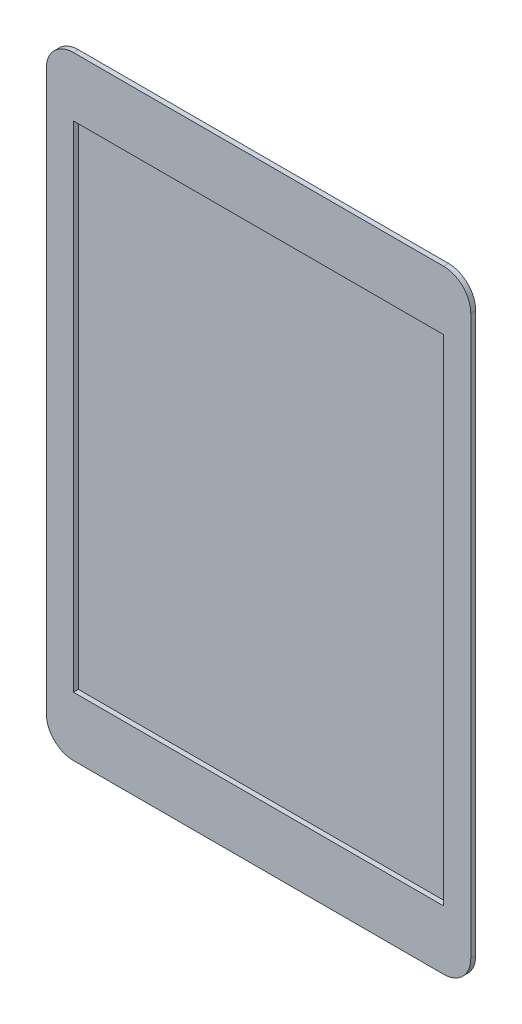
SolidWorks part; units mm, degrees
material "A-Glass Fiber"
ref_plane "Front Plane" through (0, 0, 0) normal (0, 0, 1) x (1, 0, 0)
ref_plane "Top Plane" through (0, 0, 0) normal (0, 1, 0) x (1, 0, 0)
ref_plane "Right Plane" through (0, 0, 0) normal (1, 0, 0) x (0, 0, -1)
sketch "Sketch2" plane through (0, 0, 0) normal (0, 0, 1) x (1, 0, 0)
  line L1 (-75.05, 124.3) -> (75.05, 124.3)
  line L2 (-86.05, 113.3) -> (-86.05, -113.3)
  line L3 (-75.05, -124.3) -> (75.05, -124.3)
  line L4 (86.05, 113.3) -> (86.05, -113.3)
  line L5 (-86.05, 124.3) -> (86.05, -124.3) construction
  line L6 (-86.05, -124.3) -> (86.05, 124.3) construction
  line L7 (-75.05, 100.3) -> (75.05, 100.3)
  line L8 (-75.05, 100.3) -> (-75.05, -100.3)
  line L9 (-75.05, -100.3) -> (75.05, -100.3)
  line L10 (75.05, 100.3) -> (75.05, -100.3)
  line L11 (-75.05, 100.3) -> (75.05, -100.3) construction
  line L12 (-75.05, -100.3) -> (75.05, 100.3) construction
  arc A0 (-86.05, -113.3) -> (-75.05, -124.3) centre (-75.05, -113.3) ccw
  arc A1 (75.05, -124.3) -> (86.05, -113.3) centre (75.05, -113.3) ccw
  arc A2 (75.05, 124.3) -> (86.05, 113.3) centre (75.05, 113.3) cw
  arc A3 (-75.05, 124.3) -> (-86.05, 113.3) centre (-75.05, 113.3) ccw
  point P0 (0, 0)
  point P18 (0, 0)
  dimension "D3" = 11
  dimension "D1" = 248.6
  dimension "D2" = 172.1
  dimension "D4" = 200.6
  dimension "D5" = 150.1
extrude "Boss-Extrude1" add sketch "Sketch2" along normal blind 2
sketch "Sketch3" plane through (0, 0, 0) normal (0, 0, 1) x (1, 0, 0)
  line L1 (-75.05, -100.3) -> (75.05, -100.3)
  line L2 (-75.05, -100.3) -> (-75.05, 100.3)
  line L3 (-75.05, 100.3) -> (75.05, 100.3)
  line L4 (75.05, -100.3) -> (75.05, 100.3)
  line L5 (-75.05, -100.3) -> (75.05, 100.3) construction
  line L6 (-75.05, 100.3) -> (75.05, -100.3) construction
  point P0 (0, 0)
extrude "Boss-Extrude2" add sketch "Sketch3" against normal blind 0.1 separate body
ref_plane "Plane1" through (0, 0, 0) normal (0, 0, -1) x (-1, 0, 0)
sketch "Sketch4" plane through (0, 0, 0) normal (0, 0, -1) x (-1, 0, 0)
  line L0 (75.05, -124.3) -> (-75.05, -124.3) construction
  circle A0 centre (0, -111.8) radius 4.75
  circle A1 centre (0, -111.8) radius 5.5
  dimension "D2" = 9.5
  dimension "D3" = 11
  dimension "D1" = 12.5
extrude "Cut-Extrude1" cut sketch "Sketch4" against normal blind 1
fillet "Fillet1" radius 0.001 1 edges at (-4.75, -111.8, 0)
fillet "Fillet2" radius 0.001 1 edges at (-5.5, -111.8, 0)
fillet "Fillet3" radius 0.001 1 edges at (-5.5, -111.8, 1)
fillet "Fillet4" radius 0.001 1 edges at (-4.75, -111.8, 1)
sketch "Sketch5" plane through (0, 0, 0) normal (0, 0, -1) x (-1, 0, 0)
  circle A0 centre (0, 112.8598) radius 1.5
  dimension "D1" = 3
extrude "Cut-Extrude3" cut sketch "Sketch5" against normal blind 0.5
